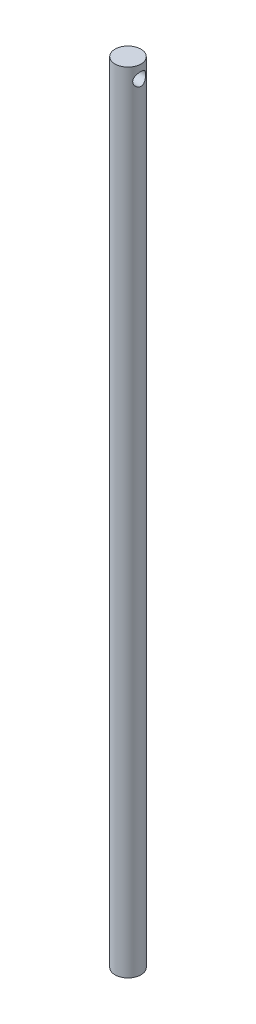
SolidWorks part; units mm, degrees
ref_plane "Front Plane" through (0, 0, 0) normal (0, 0, 1) x (1, 0, 0)
ref_plane "Top Plane" through (0, 0, 0) normal (0, 1, 0) x (1, 0, 0)
ref_plane "Right Plane" through (0, 0, 0) normal (1, 0, 0) x (0, 0, -1)
sketch "Sketch1" plane through (0, 0, 0) normal (0, 1, 0) x (1, 0, 0)
  circle A0 centre (0, 0) radius 3.175
  dimension "D1" = 6.35
extrude "Boss-Extrude1" add sketch "Sketch1" along normal blind 193.675 contours A0
sketch "Sketch2" plane through (0, 0, 0) normal (1, 0, 0) x (0, 0, -1)
  line L0 (3.175, 193.675) -> (-3.175, 193.675) construction
  circle A0 centre (0, 190.5) radius 1.5875
  dimension "D1" = 3.175
  dimension "D2" = 3.175
extrude "Cut-Extrude1" cut sketch "Sketch2" against normal blind 9.652 and the other way blind 9.398
